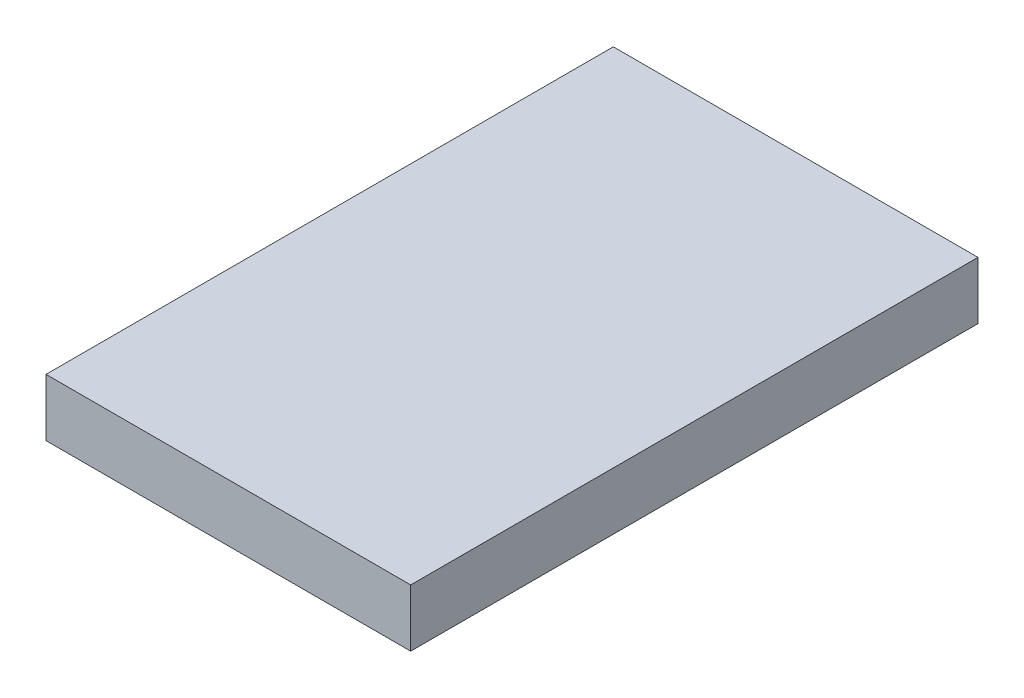
SolidWorks part; units mm, degrees
material "Custom Plastic"
ref_plane "Front Plane" through (0, 0, 0) normal (0, 0, 1) x (1, 0, 0)
ref_plane "Top Plane" through (0, 0, 0) normal (0, 1, 0) x (1, 0, 0)
ref_plane "Right Plane" through (0, 0, 0) normal (1, 0, 0) x (0, 0, -1)
sketch "Sketch1" plane through (0, 0, 0) normal (0, 1, 0) x (1, 0, 0)
  line L1 (0, 0) -> (-54, 0)
  line L2 (0, 0) -> (0, 84)
  line L3 (0, 84) -> (-54, 84)
  line L4 (-54, 0) -> (-54, 84)
  dimension "D1" = 84
  dimension "D2" = 54
extrude "Boss-Extrude1" add sketch "Sketch1" along normal blind 8.5
